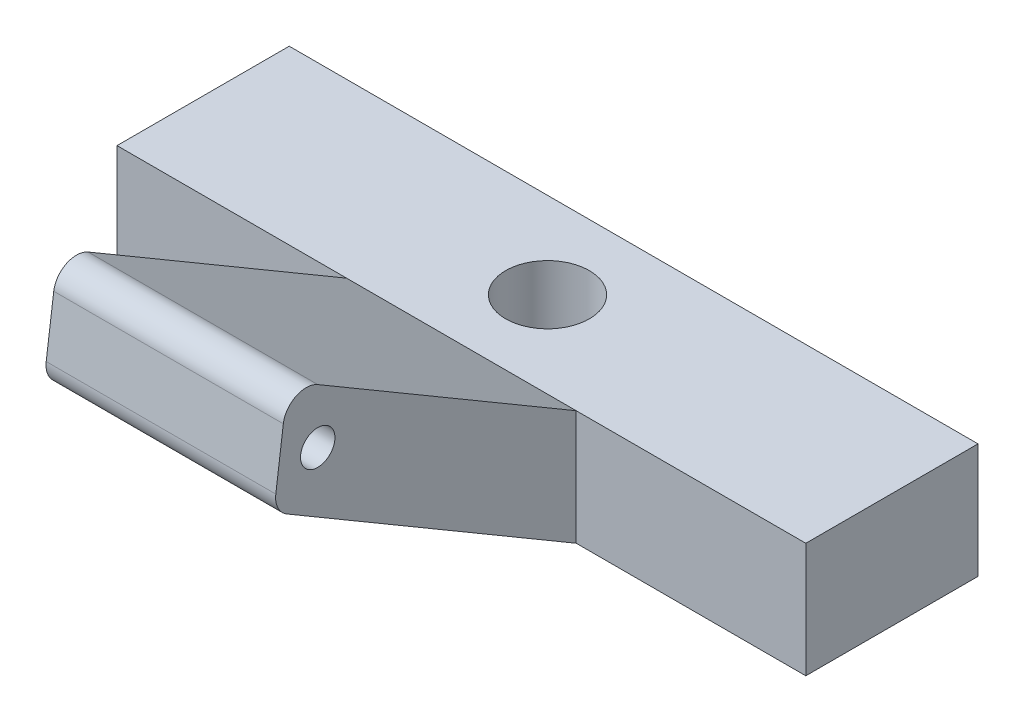
SolidWorks part; units mm, degrees
ref_plane "Plan de face" through (0, 0, 0) normal (0, 0, 1) x (1, 0, 0)
ref_plane "Plan de dessus" through (0, 0, 0) normal (0, 1, 0) x (1, 0, 0)
ref_plane "Plan de droite" through (0, 0, 0) normal (1, 0, 0) x (0, 0, -1)
sketch "Esquisse1" plane through (0, 0, 0) normal (0, 1, 0) x (1, 0, 0)
  line L6 (-30, -7.5) -> (30, -7.5)
  line L7 (-30, -7.5) -> (-30, 7.5)
  line L8 (-30, 7.5) -> (30, 7.5)
  line L9 (30, -7.5) -> (30, 7.5)
  line L10 (-30, -7.5) -> (30, 7.5) construction
  line L11 (-30, 7.5) -> (30, -7.5) construction
  circle A0 centre (0, 0) radius 3.6443
  point P2 (0, 0)
extrude "Boss.-Extru.2" add sketch "Esquisse1" along normal blind 10
sketch "Esquisse2" plane through (0, 0, 0) normal (1, 0, 0) x (0, 0, -1)
  line L0 (-7.5, 0) -> (-32.6999, 14.8076)
  line L1 (-7.5, 10) -> (-30.0164, 23.2308)
  line L2 (-33.6695, 16.7938) -> (-33.0124, 21.7683)
  line L3 (-7.5, 0) -> (-7.5, 10)
  arc A0 (-30.0164, 23.2308) -> (-33.0124, 21.7683) centre (-31.0296, 21.5064) ccw
  arc A1 (-33.6695, 16.7938) -> (-32.6999, 14.8076) centre (-31.6867, 16.5319) ccw
  circle A2 centre (-30.0164, 18.484) radius 1.5
  dimension "D1" = 2
extrude "Boss.-Extru.3" add sketch "Esquisse2" along normal blind 10 and the other way blind 10
